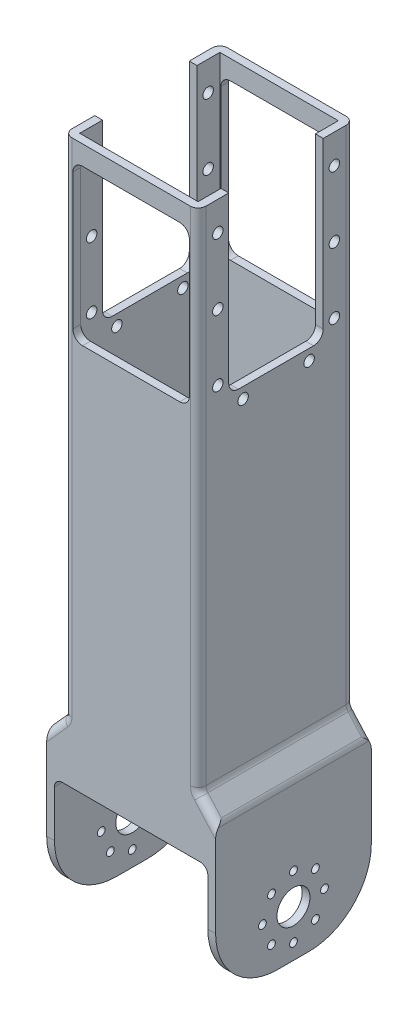
SolidWorks part; units mm, degrees
material "PLA"
ref_plane "Front Plane" through (0, 0, 0) normal (0, 0, 1) x (1, 0, 0)
ref_plane "Top Plane" through (0, 0, 0) normal (0, 1, 0) x (1, 0, 0)
ref_plane "Right Plane" through (0, 0, 0) normal (1, 0, 0) x (0, 0, -1)
sketch "Sketch1" plane through (0, 0, 0) normal (0, 1, 0) x (1, 0, 0)
  line L0 (-19.75, 18.05) -> (19.75, 18.05)
  line L1 (-21.75, -20.05) -> (21.75, -20.05)
  line L2 (-21.75, -20.05) -> (-21.75, 20.05)
  line L3 (-21.75, 20.05) -> (21.75, 20.05)
  line L4 (21.75, -20.05) -> (21.75, 20.05)
  line L5 (-21.75, -20.05) -> (21.75, 20.05) construction
  line L6 (-21.75, 20.05) -> (21.75, -20.05) construction
  line L7 (19.75, -18.05) -> (19.75, 18.05)
  line L8 (-19.75, -18.05) -> (19.75, -18.05)
  line L9 (-19.75, -18.05) -> (-19.75, 18.05)
  point P0 (0, 0)
  dimension "D1" = 43.5
  dimension "D2" = 40.1
  dimension "D3" = 2
extrude "Boss-Extrude1" add sketch "Sketch1" along normal blind 40
sketch "Sketch3" plane through (21.75, 0, 0) normal (1, 0, 0) x (0, 0, -1)
  line L0 (0, 12) -> (0, 0) construction
  line L1 (-20.05, 0) -> (20.05, 0) construction
  circle A0 centre (0, 12) radius 8 construction
  circle A1 centre (0, 20) radius 1
  circle A2 centre (5.6569, 17.6569) radius 1
  circle A3 centre (8, 12) radius 1
  circle A4 centre (5.6569, 6.3431) radius 1
  circle A5 centre (0, 4) radius 1
  circle A6 centre (-5.6569, 6.3431) radius 1
  circle A7 centre (-8, 12) radius 1
  circle A8 centre (-5.6569, 17.6569) radius 1
  circle A9 centre (0, 12) radius 4.25
  point P22 (0, 12)
  dimension "D1" = 16
  dimension "D3" = 2
  dimension "D5" = 8.5
  dimension "D2" = 12
  dimension "D4" = 8
extrude "Cut-Extrude2" cut sketch "Sketch3" against normal through all
sketch "Sketch4" plane through (0, 0, 20.05) normal (0, 0, 1) x (1, 0, 0)
  line L14 (-19.75, 40) -> (-19.75, 0)
  line L15 (-19.75, 30) -> (-19.75, 0)
  line L16 (-19.75, 30) -> (19.75, 30)
  line L17 (19.75, 40) -> (19.75, 0)
  line L18 (19.75, 30) -> (19.75, 0)
  line L19 (-19.75, 0) -> (19.75, 0)
  dimension "D3" = 30
  dimension "D1" = 2
  dimension "D2" = 2
extrude "Cut-Extrude3" cut sketch "Sketch4" against normal through all
fillet "Fillet1" radius 16 4 edges at (-20.75, 0, -20.05) (20.75, 0, -20.05) (20.75, 0, 20.05) (-20.75, 0, 20.05)
ref_plane "Plane1" through (0, 45, 0) normal (0, 1, 0) x (1, 0, 0)
sketch "Sketch7" plane through (0, 45, 0) normal (0, 1, 0) x (1, 0, 0)
  line L0 (-15.25, -18.05) -> (-15.25, 18.05) construction
  line L1 (-17.25, -20.05) -> (17.25, -20.05)
  line L2 (-17.25, -20.05) -> (-17.25, 20.05)
  line L3 (-17.25, 20.05) -> (17.25, 20.05)
  line L4 (17.25, -20.05) -> (17.25, 20.05)
  line L5 (-17.25, -20.05) -> (17.25, 20.05) construction
  line L6 (-17.25, 20.05) -> (17.25, -20.05) construction
  line L7 (-15.25, 18.05) -> (15.25, 18.05) construction
  line L8 (15.25, -18.05) -> (15.25, 18.05) construction
  line L9 (-15.25, -18.05) -> (15.25, -18.05) construction
  point P0 (0, 0)
  dimension "D1" = 34.5
  dimension "D2" = 40.1
  dimension "D3" = 2
sketch "Sketch8" plane through (0, 40, 0) normal (0, 1, 0) x (1, 0, 0)
  line L0 (-21.75, -20.05) -> (21.75, -20.05) construction
  line L1 (-19.75, -18.05) -> (19.75, -18.05) construction
  line L2 (21.75, -20.05) -> (21.75, 20.05) construction
  line L3 (19.75, -18.05) -> (19.75, 18.05) construction
  line L4 (-19.75, 18.05) -> (-19.75, -18.05) construction
  line L5 (19.75, 18.05) -> (-19.75, 18.05) construction
  line L6 (-21.75, 20.05) -> (-21.75, -20.05) construction
  line L7 (21.75, 20.05) -> (-21.75, 20.05) construction
  line L8 (-21.75, -20.05) -> (21.75, -20.05)
  line L9 (-19.75, -18.05) -> (19.75, -18.05) construction
  line L10 (21.75, -20.05) -> (21.75, 20.05)
  line L11 (19.75, -18.05) -> (19.75, 18.05) construction
  line L12 (-19.75, 18.05) -> (-19.75, -18.05) construction
  line L13 (19.75, 18.05) -> (-19.75, 18.05) construction
  line L14 (-21.75, 20.05) -> (-21.75, -20.05)
  line L15 (21.75, 20.05) -> (-21.75, 20.05)
loft "Loft2" add profiles "Sketch8", "Sketch7"
ref_plane "Plane2" through (0, 40, 0) normal (0, 1, 0) x (1, 0, 0)
sketch "Sketch10" plane through (0, 40, 0) normal (0, 1, 0) x (1, 0, 0)
  line L0 (-19.75, -18.05) -> (19.75, -18.05)
  line L1 (19.75, -18.05) -> (19.75, 18.05)
  line L2 (-19.75, 18.05) -> (-19.75, -18.05)
  line L3 (19.75, 18.05) -> (-19.75, 18.05)
  line L4 (-19.75, 18.05) -> (19.75, -18.05) construction
  point P4 (0, 0)
  dimension "D1" = 39.5
  dimension "D2" = 36.1
sketch "Sketch11" plane through (0, 45, 0) normal (0, 1, 0) x (1, 0, 0)
  line L0 (-15.25, -18.05) -> (-15.25, 18.05)
  line L1 (-15.25, 18.05) -> (15.25, 18.05)
  line L2 (15.25, -18.05) -> (15.25, 18.05)
  line L3 (-15.25, -18.05) -> (15.25, -18.05)
  line L4 (-15.25, 18.05) -> (15.25, -18.05) construction
  line L5 (-15.25, -18.05) -> (15.25, 18.05) construction
  point P4 (0, 0)
  dimension "D1" = 36.1
  dimension "D2" = 30.5
loft "Cut-Loft1" cut profiles "Sketch11", "Sketch10"
sketch "Sketch12" plane through (0, 45, 0) normal (0, 1, 0) x (1, 0, 0)
  line L0 (-17.25, 20.05) -> (-17.25, -20.05) construction
  line L1 (-17.25, -20.05) -> (17.25, -20.05) construction
  line L2 (17.25, -20.05) -> (17.25, 20.05) construction
  line L3 (17.25, 20.05) -> (-17.25, 20.05) construction
  line L4 (-17.25, 20.05) -> (-17.25, -20.05)
  line L5 (-17.25, -20.05) -> (17.25, -20.05)
  line L6 (17.25, -20.05) -> (17.25, 20.05)
  line L7 (17.25, 20.05) -> (-17.25, 20.05)
  line L8 (-15.25, -18.05) -> (15.25, -18.05) construction
  line L9 (15.25, -18.05) -> (15.25, 18.05) construction
  line L10 (-15.25, 18.05) -> (-15.25, -18.05) construction
  line L11 (15.25, 18.05) -> (-15.25, 18.05) construction
  line L12 (-15.25, -18.05) -> (15.25, -18.05)
  line L13 (15.25, -18.05) -> (15.25, 18.05)
  line L14 (-15.25, 18.05) -> (-15.25, -18.05)
  line L15 (15.25, 18.05) -> (-15.25, 18.05)
extrude "Boss-Extrude2" add sketch "Sketch12" along normal blind 130
sketch "Sketch5" plane through (-17.25, 0, 0) normal (-1, 0, 0) x (0, 0, 1)
  line L0 (-20.05, 175) -> (20.05, 175) construction
  line L1 (-12.1682, 175) -> (12.1682, 175)
  line L2 (-12.1682, 175) -> (-12.1682, 130)
  line L3 (-12.1682, 130) -> (12.1682, 130)
  line L4 (12.1682, 175) -> (12.1682, 130)
  line L5 (-12.1682, 175) -> (-20.05, 175) construction
  line L6 (-20.05, 40) -> (-20.05, 16) construction
  line L7 (20.05, 175) -> (20.05, 45) construction
  dimension "D1" = 45
  dimension "D2" = 24.3365
  dimension "D3" = 7.8818
extrude "Cut-Extrude4" cut sketch "Sketch5" against normal through all and the other way through all
sketch "Sketch6" plane through (0, 0, 20.05) normal (0, 0, 1) x (1, 0, 0)
  line L0 (-15, 150) -> (-21.75, 150) construction
  line L1 (-15, 130) -> (15, 130)
  line L2 (-15, 130) -> (-15, 170)
  line L3 (-15, 170) -> (15, 170)
  line L4 (15, 130) -> (15, 170)
  line L5 (-15, 130) -> (15, 170) construction
  line L6 (-15, 170) -> (15, 130) construction
  line L7 (-21.75, 40) -> (-21.75, 16) construction
  line L8 (15, 150) -> (21.75, 150) construction
  line L9 (21.75, 40) -> (21.75, 16) construction
  line L10 (0, 150) -> (0, 175) construction
  line L11 (-17.25, 175) -> (17.25, 175) construction
  point P0 (0, 150)
  dimension "D1" = 30
  dimension "D2" = 40
  dimension "D3" = 25
extrude "Cut-Extrude5" cut sketch "Sketch6" against normal through all
fillet "Fillet2" radius 2 16 edges at (-19.75, 30, -19.05) (19.75, 30, -19.05) (19.75, 30, 19.05) (-19.75, 30, 19.05) (21.75, 40, 0) (-21.75, 40, 0)
fillet "Fillet3" radius 2.5 16 edges at (16.25, 130, -12.1682) (16.25, 130, 12.1682) (-15, 170, -19.05) (-15, 130, -19.05) (-16.25, 130, 12.1682) (-16.25, 130, -12.1682) (15, 130, -19.05) (15, 170, -19.05) (15, 170, 19.05) (-15, 170, 19.05) (-15, 130, 19.05) (15, 130, 19.05)
sketch "Sketch16" plane through (-17.25, 0, 0) normal (-1, 0, 0) x (0, 0, 1)
  line L0 (-15.0318, 167.5) -> (-15.0318, 127.2) construction
  line L1 (-15.0318, 127.2) -> (14.9682, 127.2) construction
  line L2 (14.9682, 127.2) -> (14.9682, 167.5) construction
  line L3 (-18.05, 175) -> (-12.1682, 175) construction
  line L4 (12.1682, 175) -> (18.05, 175) construction
  line L5 (-12.1682, 132.5) -> (-12.1682, 175) construction
  circle A1 centre (-15.0318, 167.5) radius 1.35
  circle A3 centre (-15.0318, 150.5) radius 1.35
  circle A5 centre (-15.0318, 133.5) radius 1.35
  circle A7 centre (-8.5318, 127.2) radius 1.35
  circle A9 centre (8.4682, 127.2) radius 1.35
  circle A11 centre (14.9682, 133.5) radius 1.35
  circle A13 centre (14.9682, 150.5) radius 1.35
  circle A15 centre (14.9682, 167.5) radius 1.35
  dimension "D1" = 2.7
  dimension "D2" = 2.7
  dimension "D3" = 2.7
  dimension "D4" = 2.7
  dimension "D5" = 2.7
  dimension "D6" = 2.7
  dimension "D7" = 2.7
  dimension "D8" = 2.7
  dimension "D9" = 7.5
  dimension "D10" = 7.5
  dimension "D11" = 17
  dimension "D12" = 17
  dimension "D13" = 17
  dimension "D14" = 17
  dimension "D15" = 6.5
  dimension "D16" = 17
  dimension "D17" = 6.5
  dimension "D18" = 6.3
  dimension "D19" = 2.8635
extrude "Cut-Extrude6" cut sketch "Sketch16" against normal through all
